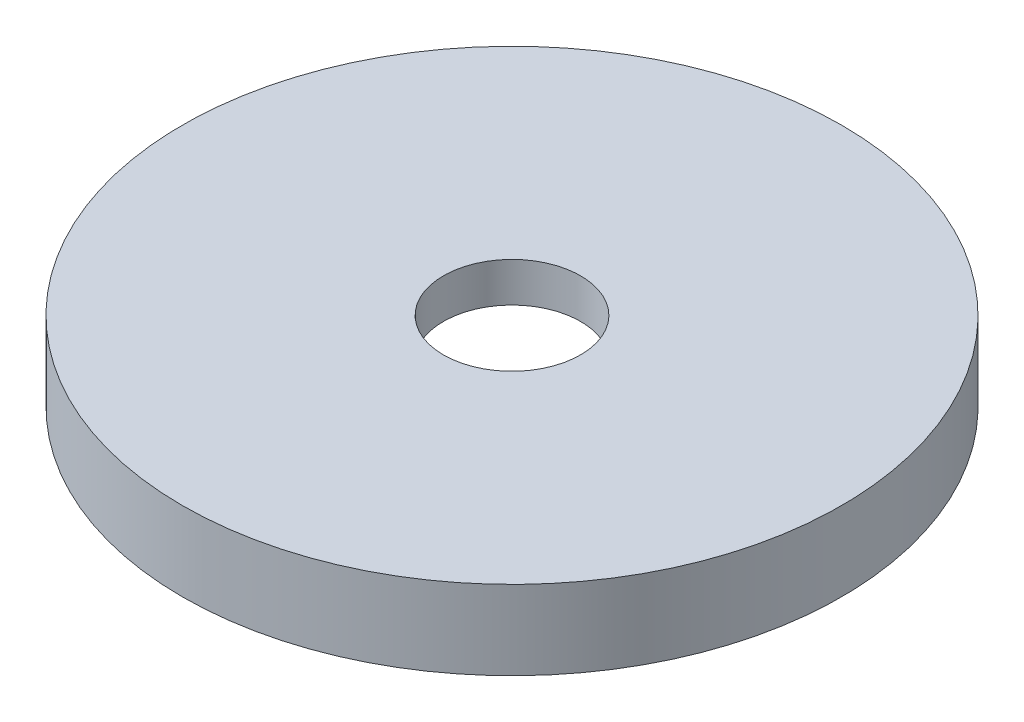
SolidWorks part; units mm, degrees
ref_plane "Front Plane" through (0, 0, 0) normal (0, 0, 1) x (1, 0, 0)
ref_plane "Top Plane" through (0, 0, 0) normal (0, 1, 0) x (1, 0, 0)
ref_plane "Right Plane" through (0, 0, 0) normal (1, 0, 0) x (0, 0, -1)
sketch "Sketch1" plane through (0, 0, 0) normal (0, 1, 0) x (1, 0, 0)
  circle A0 centre (0, 0) radius 12.5
  circle A1 centre (0, 0) radius 10
  dimension "D1" = 20
  dimension "D2" = 25
extrude "Boss-Extrude1" add sketch "Sketch1" along normal blind 1.5
sketch "Sketch2" plane through (0, 1.5, 0) normal (0, 1, 0) x (1, 0, 0)
  circle A0 centre (0, 0) radius 12.5
  dimension "D1" = 25
extrude "Boss-Extrude2" add sketch "Sketch2" along normal blind 1.5
sketch "Sketch3" plane through (0, 3, 0) normal (0, 1, 0) x (1, 0, 0)
  circle A0 centre (0, 0) radius 2.6
  dimension "D1" = 5.2
extrude "Cut-Extrude1" cut sketch "Sketch3" against normal blind 2
